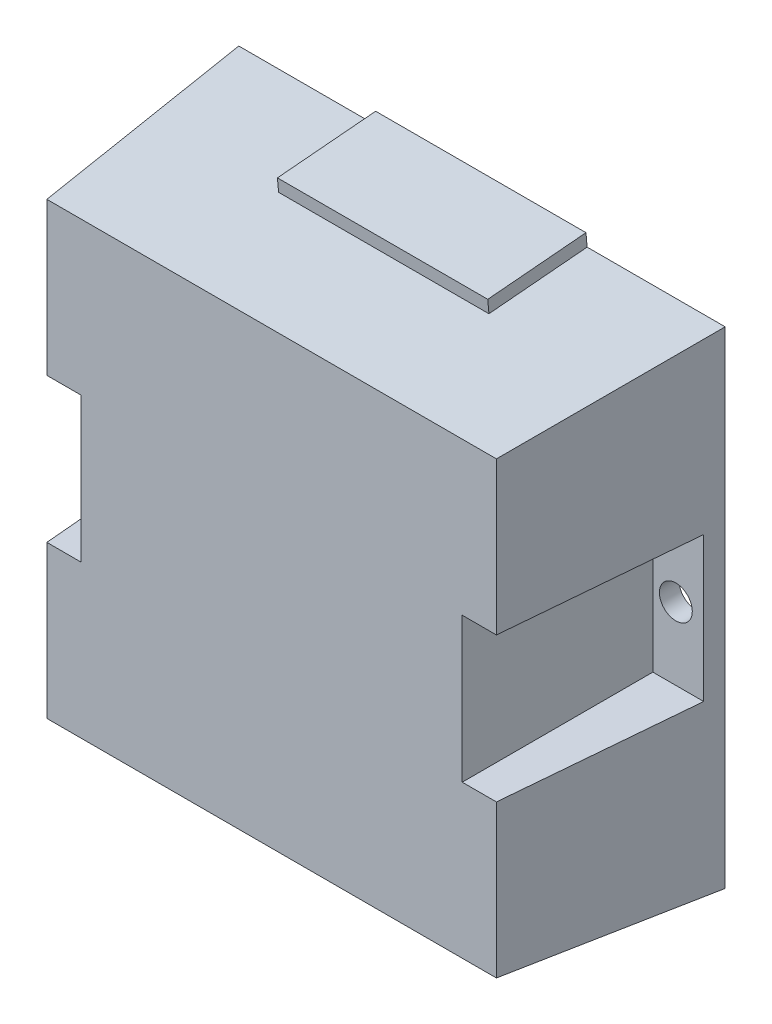
SolidWorks part; units mm, degrees
ref_plane "Plan de face" through (0, 0, 0) normal (0, 0, 1) x (1, 0, 0)
ref_plane "Plan de dessus" through (0, 0, 0) normal (0, 1, 0) x (1, 0, 0)
ref_plane "Plan de droite" through (0, 0, 0) normal (1, 0, 0) x (0, 0, -1)
sketch "Esquisse1" plane through (0, 0, 0) normal (0, 0, 1) x (1, 0, 0)
  line L1 (-172.1064, -6.317) -> (-98.1064, -6.317)
  line L2 (-172.1064, -6.317) -> (-172.1064, 67.683)
  line L3 (-172.1064, 67.683) -> (-98.1064, 67.683)
  line L4 (-98.1064, -6.317) -> (-98.1064, 67.683)
  dimension "D1" = 74
  dimension "D2" = 74
extrude "Boss.-Extru.1" add sketch "Esquisse1" along normal blind 32 draft 5
sketch "Esquisse2" plane through (0, 0, 32) normal (0, 0, 1) x (1, 0, 0)
  line L0 (-172.1064, 67.683) -> (-172.1064, -6.317) construction
  line L1 (-184.0491, 41.683) -> (-164.1064, 41.683)
  line L2 (-184.0491, 41.683) -> (-184.0491, 19.683)
  line L3 (-184.0491, 19.683) -> (-164.1064, 19.683)
  line L4 (-164.1064, 41.683) -> (-164.1064, 19.683)
  line L5 (-106.1064, 41.683) -> (-90.1724, 41.683)
  line L6 (-106.1064, 41.683) -> (-106.1064, 19.683)
  line L7 (-106.1064, 19.683) -> (-90.1724, 19.683)
  line L8 (-90.1724, 41.683) -> (-90.1724, 19.683)
  line L9 (-98.1064, -6.317) -> (-98.1064, 67.683) construction
  line L10 (-172.1064, -6.317) -> (-98.1064, -6.317) construction
  dimension "D1" = 8
  dimension "D2" = 8
  dimension "D3" = 26
  dimension "D4" = 22
extrude "Enlèv. mat.-Extru.1" cut sketch "Esquisse2" against normal blind 29
sketch "Esquisse3" plane through (0, 0, 3) normal (0, 0, 1) x (1, 0, 0)
  line L0 (-98.1064, 67.683) -> (-172.1064, 67.683) construction
  line L1 (-98.1064, -6.317) -> (-98.1064, 67.683) construction
  line L2 (-172.1064, 67.683) -> (-172.1064, -6.317) construction
  circle A0 centre (-167.6064, 30.683) radius 2.5
  circle A1 centre (-102.6064, 30.683) radius 2.5
  dimension "D1" = 5
  dimension "D2" = 5
  dimension "D3" = 37
  dimension "D4" = 4.5
  dimension "D5" = 4.5
extrude "Enlèv. mat.-Extru.2" cut sketch "Esquisse3" against normal blind 10
sketch "Esquisse5" plane through (0, 67.1688, 5.8765) normal (0, 0.9962, 0.0872) x (1, 0, 0)
  line L0 (-98.1064, 5.899) -> (-172.1064, 5.899) construction
  line L1 (-151.1064, 5.899) -> (-119.1064, 5.899)
  line L2 (-151.1064, 5.899) -> (-151.1064, -9.101)
  line L3 (-151.1064, -9.101) -> (-119.1064, -9.101)
  line L4 (-119.1064, 5.899) -> (-119.1064, -9.101)
  dimension "D1" = 32
  dimension "D2" = 21
  dimension "D3" = 15
extrude "Boss.-Extru.2" add sketch "Esquisse5" along normal blind 2
